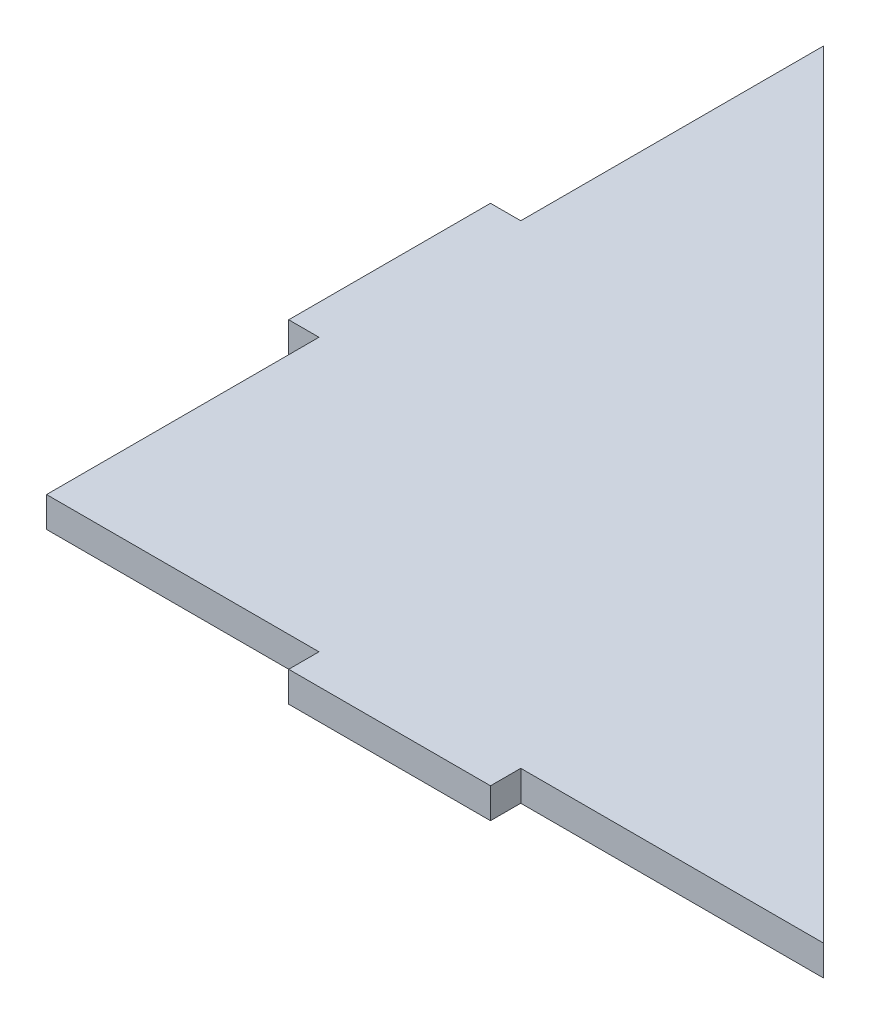
SolidWorks part; units mm, degrees
ref_plane "Alzado" through (0, 0, 0) normal (0, 0, 1) x (1, 0, 0)
ref_plane "Planta" through (0, 0, 0) normal (0, 1, 0) x (1, 0, 0)
ref_plane "Vista lateral" through (0, 0, 0) normal (1, 0, 0) x (0, 0, -1)
sketch "Croquis1" plane through (0, 0, 0) normal (0, 1, 0) x (1, 0, 0)
  line L0 (0, 0) -> (27, 0)
  line L1 (0, 0) -> (0, 27)
  line L2 (0, 77) -> (77, 0)
  line L4 (37, -3) -> (47, -3)
  line L5 (47, -3) -> (47, 0)
  line L6 (37, -3) -> (27, -3)
  line L7 (27, -3) -> (27, 0)
  line L8 (47, 0) -> (77, 0)
  line L9 (-3, 37) -> (-3, 47)
  line L10 (-3, 37) -> (-3, 27)
  line L11 (-3, 47) -> (0, 47)
  line L12 (-3, 27) -> (0, 27)
  line L13 (0, 47) -> (0, 77)
  dimension "D1" = 27
  dimension "D2" = 30
  dimension "D3" = 30
  dimension "D4" = 10
  dimension "D5" = 10
  dimension "D6" = 27
  dimension "D7" = 10
  dimension "D8" = 10
extrude "Saliente-Extruir1" add sketch "Croquis1" along normal blind 3
